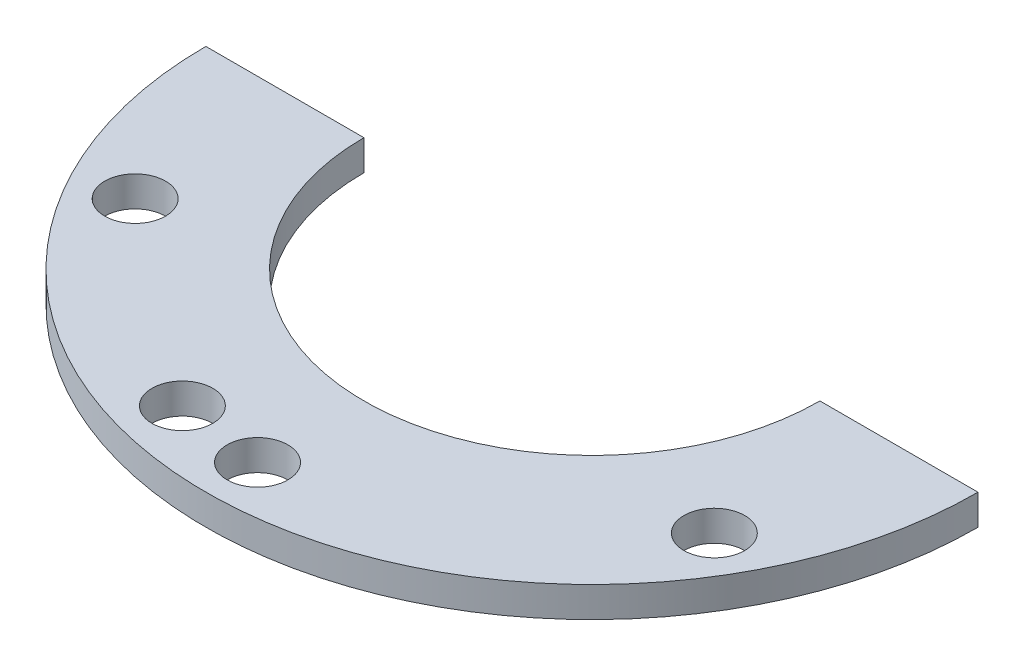
SolidWorks part; units mm, degrees
material "ABS"
ref_plane "Front Plane" through (0, 0, 0) normal (0, 0, 1) x (1, 0, 0)
ref_plane "Top Plane" through (0, 0, 0) normal (0, 1, 0) x (1, 0, 0)
ref_plane "Right Plane" through (0, 0, 0) normal (1, 0, 0) x (0, 0, -1)
sketch "Sketch1" plane through (0, 0, 0) normal (0, 1, 0) x (1, 0, 0)
  circle A0 centre (0, 0) radius 12.7
  dimension "D1" = 25.4
extrude "Boss-Extrude1" add sketch "Sketch1" along normal blind 1
sketch "Sketch19" plane through (0, 1, 0) normal (0, 1, 0) x (1, 0, 0)
  circle A0 centre (0, 11) radius 1
  circle A1 centre (9.5263, 5.5) radius 1
  circle A2 centre (9.5263, -5.5) radius 1
  circle A3 centre (0, -11) radius 1
  circle A4 centre (-9.5263, -5.5) radius 1
  circle A5 centre (-9.5263, 5.5) radius 1
  point P13 (0, 0)
  dimension "D1" = 2
  dimension "D2" = 11
  dimension "D3" = 6
extrude "Cut-Extrude1" cut sketch "Sketch19" against normal through all both and the other way through all
sketch "Sketch20" plane through (0, 1, 0) normal (0, 1, 0) x (1, 0, 0)
  circle A0 centre (0, 0) radius 7.5
  dimension "D1" = 15
extrude "Cut-Extrude2" cut sketch "Sketch20" against normal through all both and the other way through all
sketch "Sketch21" plane through (0, 0, 0) normal (0, 0, 1) x (1, 0, 0)
  line L1 (-36.7533, 32.3113) -> (29.1209, 32.3113)
  line L2 (-36.7533, 32.3113) -> (-36.7533, -19.668)
  line L3 (-36.7533, -19.668) -> (29.1209, -19.668)
  line L4 (29.1209, 32.3113) -> (29.1209, -19.668)
extrude "Cut-Extrude3" cut sketch "Sketch21" against normal through all
sketch "Sketch23" plane through (0, 1, 0) normal (0, 1, 0) x (1, 0, 0)
  line L0 (9.5263, -5.5) -> (0, -11)
  line L1 (0, 0) -> (4.7631, -8.25) construction
  line L2 (4.7631, -8.25) -> (0, 0) construction
  line L3 (0, 0) -> (-4.7287, -17.6476) construction
  circle A0 centre (-2.847, -10.6252) radius 1
  dimension "D1" = 2
  dimension "D2" = 11
  dimension "D3" = 45
extrude "Cut-Extrude4" cut sketch "Sketch23" against normal through all both and the other way through all contours A0
